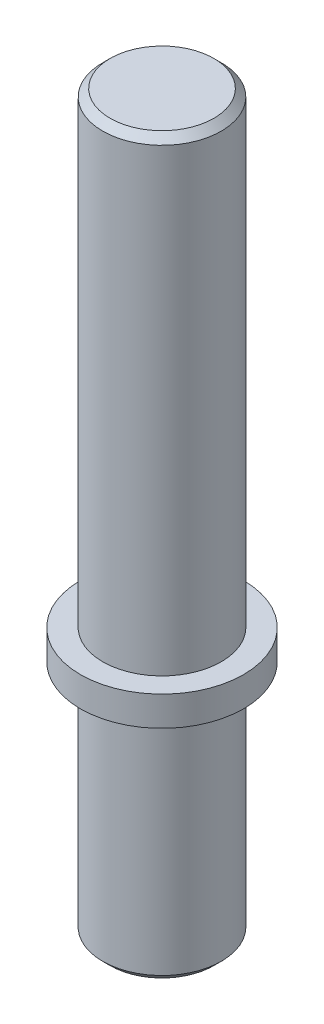
SolidWorks part; units mm, degrees
ref_plane "Front Plane" through (0, 0, 0) normal (0, 0, 1) x (1, 0, 0)
ref_plane "Top Plane" through (0, 0, 0) normal (0, 1, 0) x (1, 0, 0)
ref_plane "Right Plane" through (0, 0, 0) normal (1, 0, 0) x (0, 0, -1)
sketch "Sketch1" plane through (0, 0, 0) normal (0, 1, 0) x (1, 0, 0)
  circle A0 centre (0, 0) radius 4
  dimension "D1" = 8
extrude "Boss-Extrude1" add sketch "Sketch1" along normal blind 16
sketch "Sketch2" plane through (0, 16, 0) normal (0, 1, 0) x (1, 0, 0)
  circle A0 centre (0, 0) radius 5.5
  dimension "D1" = 11
extrude "Boss-Extrude2" add sketch "Sketch2" along normal blind 2
sketch "Sketch3" plane through (0, 18, 0) normal (0, 1, 0) x (1, 0, 0)
  circle A0 centre (0, 0) radius 4
  dimension "D1" = 8
extrude "Boss-Extrude3" add sketch "Sketch3" along normal blind 31.5
chamfer "Chamfer1" distance 0.5 angle 45 2 edges at (0, 49.5, 4) (0, 0, 4)
